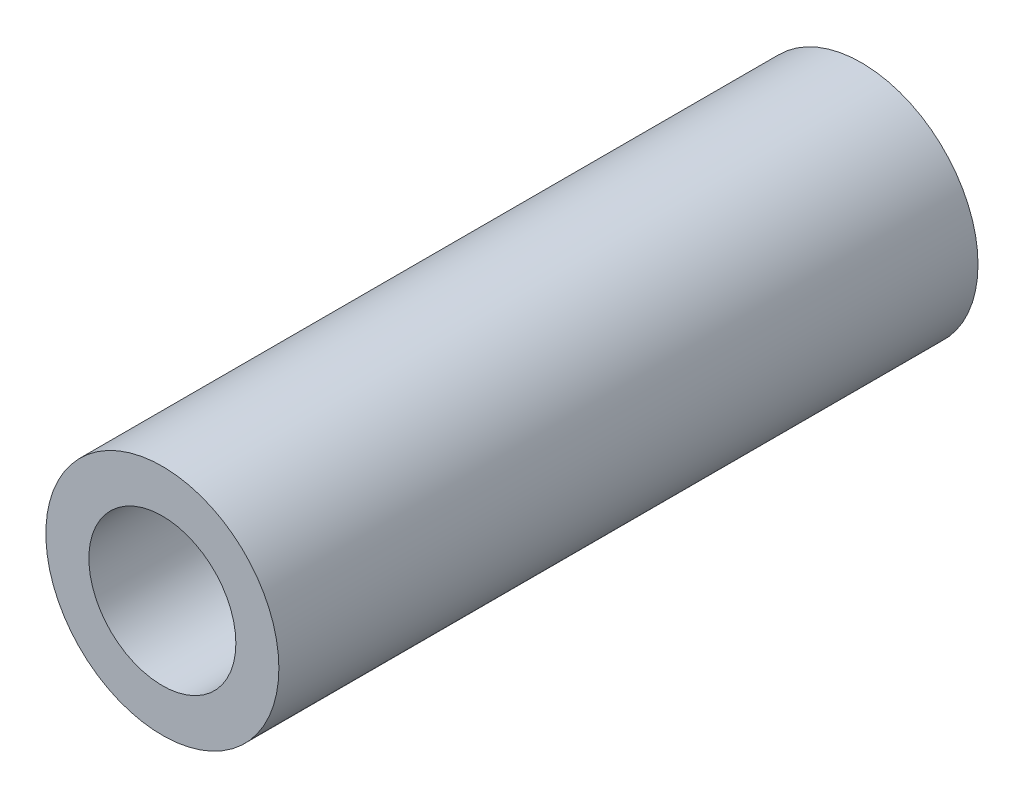
SolidWorks part; units mm, degrees
ref_plane "Alzado" through (0, 0, 0) normal (0, 0, 1) x (1, 0, 0)
ref_plane "Planta" through (0, 0, 0) normal (0, 1, 0) x (1, 0, 0)
ref_plane "Vista lateral" through (0, 0, 0) normal (1, 0, 0) x (0, 0, -1)
sketch "Croquis1" plane through (0, 0, 0) normal (0, 0, 1) x (1, 0, 0)
  circle A0 centre (0, 0) radius 3.25
  circle A1 centre (0, 0) radius 2.05
  dimension "D1" = 6.5
  dimension "D2" = 4.1
extrude "Saliente-Extruir1" add sketch "Croquis1" along normal blind 19.5
